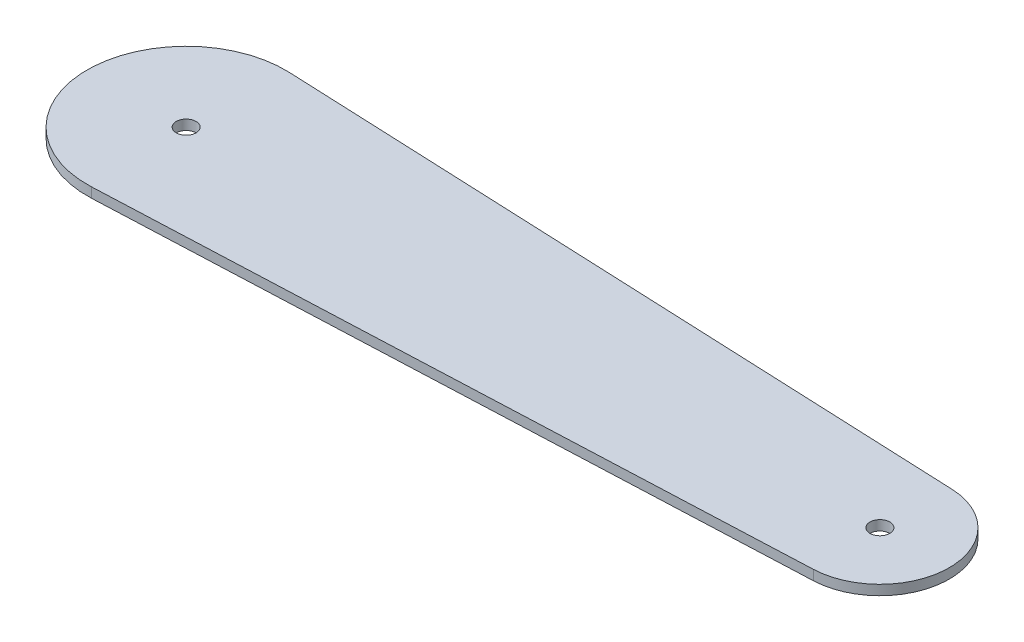
SolidWorks part; units mm, degrees
ref_plane "Front Plane" through (0, 0, 0) normal (0, 0, 1) x (1, 0, 0)
ref_plane "Top Plane" through (0, 0, 0) normal (0, 1, 0) x (1, 0, 0)
ref_plane "Right Plane" through (0, 0, 0) normal (1, 0, 0) x (0, 0, -1)
sketch "Sketch1" plane through (0, 0, 0) normal (0, 1, 0) x (1, 0, 0)
  line L0 (0, 0) -> (350, 0) construction
  line L1 (2.1429, 49.9541) -> (351.5, 34.9678)
  line L2 (2.1429, -49.9541) -> (351.5, -34.9678)
  circle A0 centre (0, 0) radius 5
  arc A1 (2.1429, 49.9541) -> (2.1429, -49.9541) centre (0, 0) ccw
  arc A2 (351.5, -34.9678) -> (351.5, 34.9678) centre (350, 0) ccw
  circle A3 centre (350, 0) radius 5
  dimension "D1" = 10
  dimension "D2" = 100
  dimension "D4" = 70
  dimension "D5" = 10
  dimension "D3" = 350
extrude "Boss-Extrude1" add sketch "Sketch1" along normal blind 5 contours L1 A2 L2 A1
